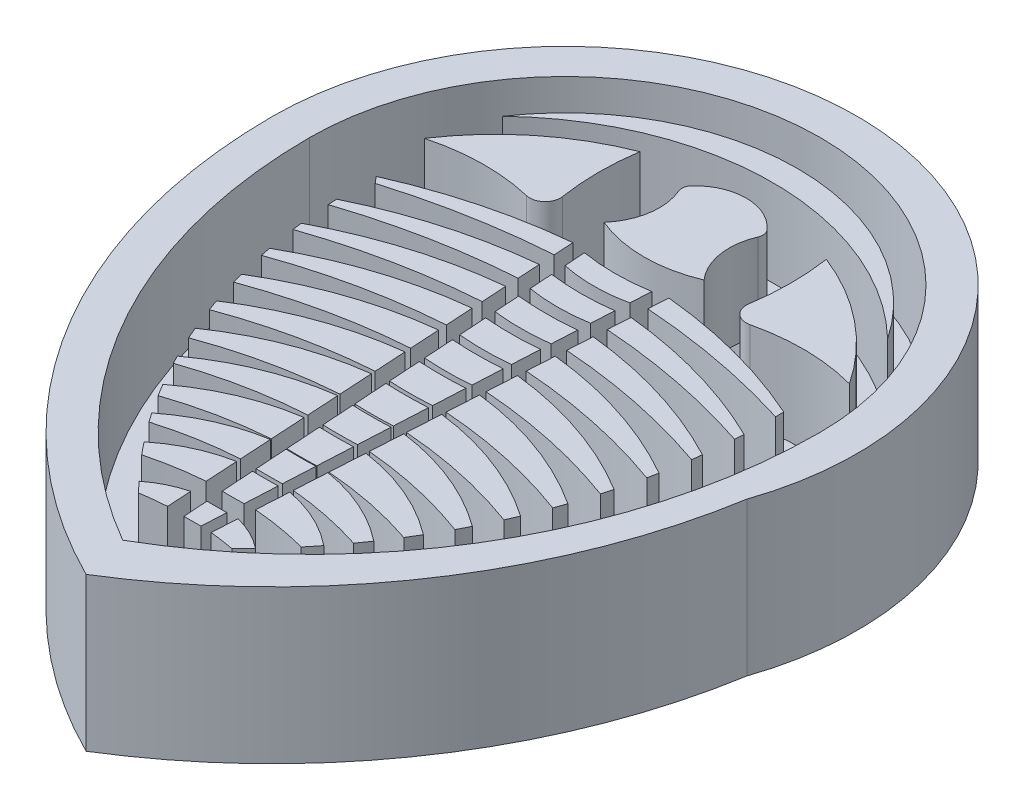
SolidWorks part; units mm, degrees
ref_plane "Přední rovina" through (0, 0, 0) normal (0, 0, 1) x (1, 0, 0)
ref_plane "Horní rovina" through (0, 0, 0) normal (0, 1, 0) x (1, 0, 0)
ref_plane "Pravá rovina" through (0, 0, 0) normal (1, 0, 0) x (0, 0, -1)
sketch "Skica1" plane through (0, 0, 0) normal (0, 1, 0) x (1, 0, 0)
  line L0 (3.5212, 0.7459) -> (3.5212, -1.0568)
  line L1 (2.9157, -3.7821) -> (1.736, -4.9619)
  line L2 (-3.4891, 0.7312) -> (-3.4891, -1.0783)
  line L3 (-1.7389, -4.9589) -> (-2.9157, -3.7821)
  line L7 (-3.4144, 2.0461) -> (3.4576, 2.0461)
  arc A0 (5, 0) -> (-5, 0) centre (0, 0) ccw
  arc A1 (-5, 0) -> (0, -8.6603) centre (5, 0) ccw
  arc A2 (0, -8.6603) -> (5, 0) centre (-5, 0) ccw
  arc A3 (1.736, -4.9619) -> (3.5212, 0.7459) centre (4.6199, -2.7308) cw
  arc A4 (2.9157, -3.7821) -> (3.5212, -1.0568) centre (4.6199, -2.7308) cw
  arc A5 (-3.4891, -1.0783) -> (-2.9157, -3.7821) centre (-4.6199, -2.7308) cw
  arc A6 (-3.4891, 0.7312) -> (-1.7389, -4.9589) centre (-4.6199, -2.7308) cw
  spline S0 degree 2 poles (-3.4144, 2.0461) (0.0191, 3.7316) (3.4576, 2.0461) knots 0 0 0 1 1 1
  dimension "D1" = 10
extrude "Přidat vysunutím1" add sketch "Skica1" against normal blind 1
sketch "Skica2" plane through (0, 0, 0) normal (0, 1, 0) x (1, 0, 0)
  line L0 (-0.9396, 1.0946) -> (-0.9163, 0.7054)
  line L1 (0.9396, 1.0946) -> (0.9163, 0.7054)
  line L2 (-0.4639, -6.8657) -> (-0.435, -7.3481)
  line L3 (-0.521, -5.9092) -> (-0.4831, -6.5437)
  line L4 (0.521, -5.9092) -> (0.4831, -6.5437)
  line L5 (-0.5631, -5.2058) -> (-0.5258, -5.8294)
  line L6 (-0.605, -4.5041) -> (-0.5642, -5.1865)
  line L7 (0.605, -4.5041) -> (0.5642, -5.1865)
  line L8 (0.6469, -3.8031) -> (0.6088, -4.4409)
  line L9 (-0.6469, -3.8031) -> (-0.6097, -4.4257)
  line L10 (-0.6887, -3.1028) -> (-0.6498, -3.7549)
  line L11 (0.6887, -3.1028) -> (0.6498, -3.7549)
  line L12 (0.7306, -2.4028) -> (0.6935, -3.0231)
  line L13 (-0.7306, -2.4028) -> (-0.6935, -3.0231)
  line L14 (-0.7724, -1.703) -> (-0.7376, -2.2844)
  line L15 (0.7724, -1.703) -> (0.7376, -2.2844)
  line L16 (0.8142, -1.0034) -> (0.7821, -1.5408)
  line L17 (-0.8142, -1.0034) -> (-0.7821, -1.5408)
  line L18 (-0.856, -0.304) -> (-0.8267, -0.7938)
  line L19 (0.856, -0.304) -> (0.8267, -0.7938)
  line L20 (0.8978, 0.3954) -> (0.8715, -0.0448)
  line L21 (-0.8978, 0.3954) -> (-0.8715, -0.0448)
  line L22 (0.4639, -6.8657) -> (0.434, -7.3648)
  line L23 (0.5631, -5.2058) -> (0.5249, -5.8452)
  line L24 (-0.6539, 1.0367) -> (-0.6272, 0.6279)
  line L25 (0.6621, 1.0381) -> (0.641, 0.6309)
  line L26 (-0.6089, 0.3483) -> (-0.5795, -0.1033)
  line L27 (0.6264, 0.3507) -> (0.6031, -0.0994)
  line L28 (0.5906, -0.3401) -> (0.5649, -0.8356)
  line L29 (-0.5638, -0.3429) -> (-0.5314, -0.8398)
  line L30 (0.5547, -1.0329) -> (0.5266, -1.5735)
  line L31 (-0.5186, -1.0361) -> (-0.4832, -1.5778)
  line L32 (-0.4732, -1.7307) -> (-0.4351, -2.3147)
  line L33 (0.5186, -1.7274) -> (0.4884, -2.3105)
  line L34 (-0.4279, -2.4264) -> (-0.3873, -3.0482)
  line L35 (0.4826, -2.4231) -> (0.4504, -3.0442)
  line L36 (-0.3369, -3.8204) -> (-0.2962, -4.4435)
  line L37 (0.4103, -3.8173) -> (0.378, -4.4401)
  line L38 (0.4464, -3.1197) -> (0.4126, -3.7721)
  line L39 (-0.3824, -3.123) -> (-0.3398, -3.7759)
  line L40 (0.3377, -5.2158) -> (0.3054, -5.8391)
  line L41 (-0.2456, -5.2184) -> (-0.205, -5.8419)
  line L42 (0.374, -4.5159) -> (0.3387, -5.1981)
  line L43 (-0.2913, -4.5188) -> (-0.2468, -5.2012)
  line L44 (-0.1999, -5.9198) -> (-0.1585, -6.554)
  line L45 (0.3013, -5.9174) -> (0.2685, -6.5517)
  line L46 (-0.1376, -6.874) -> (-0.1061, -7.3562)
  line L47 (0.2518, -6.8721) -> (0.2268, -7.3544)
  arc A0 (3.7723, 2.5471) -> (-3.7723, 2.5471) centre (0, 0) ccw
  arc A1 (3.7723, 2.5471) -> (-3.7723, 2.5471) centre (0, -1.3616) ccw
  arc A2 (-1.826, 3.293) -> (-4.1627, 1.4083) centre (0, -1.3616) ccw
  arc A7 (4.1627, 1.4083) -> (2.1882, 1.4375) centre (3.118, -2.4529) ccw
  arc A8 (-1.826, 3.293) -> (-1.8221, 1.7756) centre (3.118, 2.5471) ccw
  arc A9 (4.1627, 1.4083) -> (1.826, 3.293) centre (0, -1.3616) ccw
  arc A10 (1.8221, 1.7756) -> (1.826, 3.293) centre (-3.118, 2.5471) ccw
  arc A11 (-2.1882, 1.4375) -> (-1.8221, 1.7756) centre (-2.1185, 1.7293) ccw
  arc A12 (1.8221, 1.7756) -> (2.1882, 1.4375) centre (2.1185, 1.7293) ccw
  arc A13 (-2.1882, 1.4375) -> (-4.1627, 1.4083) centre (-3.118, -2.4529) ccw
  arc A15 (-0.9784, 1.7445) -> (-0.778, 3.0046) centre (-1.8819, 2.5341) ccw
  arc A16 (0.778, 3.0046) -> (0.9784, 1.7445) centre (1.8819, 2.5341) ccw
  arc A17 (-0.7425, 3.2169) -> (-0.778, 3.0046) centre (-0.594, 3.083) ccw
  arc A18 (0.778, 3.0046) -> (0.7425, 3.2169) centre (0.594, 3.083) ccw
  arc A20 (3.996, 0.288) -> (0.9396, 1.0946) centre (0, -8.6603) ccw
  arc A21 (-0.9784, 1.7445) -> (0.9784, 1.7445) centre (0, 4.0705) ccw
  arc A22 (0.7425, 3.2169) -> (-0.7425, 3.2169) centre (0, 2.5471) ccw
  arc A23 (3.989, -0.4811) -> (0.8978, 0.3954) centre (0, -8.6603) ccw
  arc A24 (3.9271, -1.2348) -> (0.856, -0.304) centre (0, -8.6603) ccw
  arc A25 (3.8134, -1.9708) -> (0.8142, -1.0034) centre (0, -8.6603) ccw
  arc A26 (3.6503, -2.6874) -> (0.7724, -1.703) centre (0, -8.6603) ccw
  arc A27 (3.4403, -3.3825) -> (0.7306, -2.4028) centre (0, -8.6603) ccw
  arc A28 (3.1856, -4.0546) -> (0.6887, -3.1028) centre (0, -8.6603) ccw
  arc A29 (2.8883, -4.702) -> (0.6469, -3.8031) centre (0, -8.6603) ccw
  arc A30 (2.5505, -5.3234) -> (0.605, -4.5041) centre (0, -8.6603) ccw
  arc A31 (2.1739, -5.9172) -> (0.5631, -5.2058) centre (0, -8.6603) ccw
  arc A32 (1.76, -6.4825) -> (0.521, -5.9092) centre (0, -8.6603) ccw
  arc A33 (1.1422, -7.2005) -> (0.4639, -6.8657) centre (0, -8.6603) ccw
  arc A34 (-4.9974, -0.2302) -> (0, -8.6603) centre (5, 0) ccw
  arc A35 (0, -8.6603) -> (4.9974, -0.2302) centre (-5, 0) ccw
  arc A36 (3.9992, 0.1259) -> (0.9163, 0.7054) centre (0, -12.6603) ccw
  arc A37 (3.9794, -0.6572) -> (0.8715, -0.0448) centre (0, -12.6603) ccw
  arc A38 (3.903, -1.4236) -> (0.8267, -0.7938) centre (0, -12.6603) ccw
  arc A39 (3.773, -2.1713) -> (0.7821, -1.5408) centre (0, -12.6603) ccw
  arc A40 (3.5921, -2.8981) -> (0.7376, -2.2844) centre (0, -12.6603) ccw
  arc A41 (3.3628, -3.6022) -> (0.6935, -3.0231) centre (0, -12.6603) ccw
  arc A42 (3.0872, -4.2819) -> (0.6498, -3.7549) centre (0, -12.6603) ccw
  arc A43 (2.7721, -4.9273) -> (0.6088, -4.4409) centre (-0.103, -12.6603) ccw
  arc A44 (2.4059, -5.5618) -> (0.5642, -5.1865) centre (0, -12.6603) ccw
  arc A45 (2.01, -6.1506) -> (0.5249, -5.8452) centre (-0.103, -12.6603) ccw
  arc A46 (1.5622, -6.7269) -> (0.4831, -6.5437) centre (0, -12.6603) ccw
  arc A47 (0.9136, -7.4357) -> (0.434, -7.3648) centre (-0.103, -12.6603) ccw
  arc A51 (0.9136, -7.4357) -> (1.1422, -7.2005) centre (-6.5, 0) ccw
  arc A52 (-0.9396, 1.0946) -> (-3.996, 0.288) centre (0, -8.6603) ccw
  arc A53 (-1.1422, -7.2005) -> (-0.9445, -7.4046) centre (6.5, 0) ccw
  arc A54 (-1.76, -6.4825) -> (-1.5622, -6.7269) centre (6.5, 0) ccw
  arc A55 (-2.1739, -5.9172) -> (-2.0475, -6.0984) centre (6.5, 0) ccw
  arc A56 (-2.5505, -5.3234) -> (-2.4059, -5.5618) centre (6.5, 0) ccw
  arc A57 (-2.8883, -4.702) -> (-2.8049, -4.8651) centre (6.5, 0) ccw
  arc A58 (-3.1856, -4.0546) -> (-3.0872, -4.2819) centre (6.5, 0) ccw
  arc A59 (-3.4403, -3.3825) -> (-3.3628, -3.6022) centre (6.5, 0) ccw
  arc A60 (-3.6503, -2.6874) -> (-3.5921, -2.8981) centre (6.5, 0) ccw
  arc A61 (-3.8134, -1.9708) -> (-3.773, -2.1713) centre (6.5, 0) ccw
  arc A62 (-3.9271, -1.2348) -> (-3.903, -1.4236) centre (6.5, 0) ccw
  arc A63 (-3.989, -0.4811) -> (-3.9794, -0.6572) centre (6.5, 0) ccw
  arc A64 (3.9992, 0.1259) -> (3.996, 0.288) centre (-6.5, 0) ccw
  arc A65 (3.9794, -0.6572) -> (3.989, -0.4811) centre (-6.5, 0) ccw
  arc A66 (3.903, -1.4236) -> (3.9271, -1.2348) centre (-6.5, 0) ccw
  arc A67 (3.773, -2.1713) -> (3.8134, -1.9708) centre (-6.5, 0) ccw
  arc A68 (3.5921, -2.8981) -> (3.6503, -2.6874) centre (-6.5, 0) ccw
  arc A69 (3.3628, -3.6022) -> (3.4403, -3.3825) centre (-6.5, 0) ccw
  arc A70 (3.0872, -4.2819) -> (3.1856, -4.0546) centre (-6.5, 0) ccw
  arc A71 (2.7721, -4.9273) -> (2.8883, -4.702) centre (-6.5, 0) ccw
  arc A72 (2.4059, -5.5618) -> (2.5505, -5.3234) centre (-6.5, 0) ccw
  arc A73 (2.01, -6.1506) -> (2.1739, -5.9172) centre (-6.5, 0) ccw
  arc A74 (1.5622, -6.7269) -> (1.76, -6.4825) centre (-6.5, 0) ccw
  arc A75 (-0.9163, 0.7054) -> (-3.9992, 0.1259) centre (0, -12.6603) ccw
  arc A76 (-0.8978, 0.3954) -> (-3.989, -0.4811) centre (0, -8.6603) ccw
  arc A77 (-0.8715, -0.0448) -> (-3.9794, -0.6572) centre (0, -12.6603) ccw
  arc A78 (-0.856, -0.304) -> (-3.9271, -1.2348) centre (0, -8.6603) ccw
  arc A79 (-0.8267, -0.7938) -> (-3.903, -1.4236) centre (0, -12.6603) ccw
  arc A80 (-0.8142, -1.0034) -> (-3.8134, -1.9708) centre (0, -8.6603) ccw
  arc A81 (-0.7821, -1.5408) -> (-3.773, -2.1713) centre (0, -12.6603) ccw
  arc A82 (-0.7724, -1.703) -> (-3.6503, -2.6874) centre (0, -8.6603) ccw
  arc A83 (-0.7376, -2.2844) -> (-3.5921, -2.8981) centre (0, -12.6603) ccw
  arc A84 (-0.7306, -2.4028) -> (-3.4403, -3.3825) centre (0, -8.6603) ccw
  arc A85 (-0.6935, -3.0231) -> (-3.3628, -3.6022) centre (0, -12.6603) ccw
  arc A86 (-0.6887, -3.1028) -> (-3.1856, -4.0546) centre (0, -8.6603) ccw
  arc A87 (-0.6498, -3.7549) -> (-3.0872, -4.2819) centre (0, -12.6603) ccw
  arc A88 (-0.6469, -3.8031) -> (-2.8883, -4.702) centre (0, -8.6603) ccw
  arc A89 (-0.6097, -4.4257) -> (-2.8049, -4.8651) centre (-0.103, -12.6603) ccw
  arc A90 (-0.605, -4.5041) -> (-2.5505, -5.3234) centre (0, -8.6603) ccw
  arc A91 (-0.5642, -5.1865) -> (-2.4059, -5.5618) centre (0, -12.6603) ccw
  arc A92 (-0.5631, -5.2058) -> (-2.1739, -5.9172) centre (0, -8.6603) ccw
  arc A93 (-0.5258, -5.8294) -> (-2.0475, -6.0984) centre (-0.103, -12.6603) ccw
  arc A94 (-0.521, -5.9092) -> (-1.76, -6.4825) centre (0, -8.6603) ccw
  arc A95 (-0.4831, -6.5437) -> (-1.5622, -6.7269) centre (0, -12.6603) ccw
  arc A96 (-0.4639, -6.8657) -> (-1.1422, -7.2005) centre (0, -8.6603) ccw
  arc A97 (-0.435, -7.3481) -> (-0.9445, -7.4046) centre (-0.103, -12.6603) ccw
  arc A98 (-3.996, 0.288) -> (-3.9992, 0.1259) centre (6.5, 0) ccw
  arc A100 (5, 0) -> (-5, 0) centre (0, 0) ccw construction
  arc A108 (-0.2913, -4.5188) -> (0.374, -4.5159) centre (0, 5) ccw
  arc A111 (-0.1376, -6.874) -> (0.2518, -6.8721) centre (0, 5) ccw
  arc A112 (-0.6539, 1.0367) -> (0.6621, 1.0381) centre (0, 5) ccw
  arc A113 (-0.5186, -1.0361) -> (0.5547, -1.0329) centre (0, 5) ccw
  arc A114 (-0.4732, -1.7307) -> (0.5186, -1.7274) centre (0, 5) ccw
  arc A115 (-0.5795, -0.1033) -> (0.6031, -0.0994) centre (0, 3.5471) ccw
  arc A116 (-0.6089, 0.3483) -> (0.6264, 0.3507) centre (0, 5) ccw
  arc A117 (-0.5638, -0.3429) -> (0.5906, -0.3401) centre (0, 5) ccw
  arc A118 (-0.4279, -2.4264) -> (0.4826, -2.4231) centre (0, 5) ccw
  arc A119 (-0.4351, -2.3147) -> (0.4884, -2.3105) centre (0, 3.5471) ccw
  arc A120 (-0.3873, -3.0482) -> (0.4504, -3.0442) centre (0, 3.5471) ccw
  arc A121 (-0.3824, -3.123) -> (0.4464, -3.1197) centre (0, 5) ccw
  arc A122 (-0.3369, -3.8204) -> (0.4103, -3.8173) centre (0, 5) ccw
  arc A123 (-0.1999, -5.9198) -> (0.3013, -5.9174) centre (0, 5) ccw
  arc A124 (-0.2456, -5.2184) -> (0.3377, -5.2158) centre (0, 5) ccw
  arc A125 (-0.1585, -6.554) -> (0.2685, -6.5517) centre (0, 3.5471) ccw
  arc A129 (-3.9876, 0.2918) -> (-3.8789, 0.163) centre (0, 3.5471) ccw
  arc A134 (-0.2468, -5.2012) -> (0.3387, -5.1981) centre (0, 3.5471) ccw
  arc A138 (-0.6272, 0.6279) -> (0.641, 0.6309) centre (0, 3.5471) ccw
  arc A139 (-0.4832, -1.5778) -> (0.5266, -1.5735) centre (0, 3.5471) ccw
  arc A140 (-0.2962, -4.4435) -> (0.378, -4.4401) centre (0, 3.5471) ccw
  arc A141 (-0.5314, -0.8398) -> (0.5649, -0.8356) centre (0, 3.5471) ccw
  arc A142 (-0.3398, -3.7759) -> (0.4126, -3.7721) centre (0, 3.5471) ccw
  arc A143 (-0.205, -5.8419) -> (0.3054, -5.8391) centre (0, 3.5471) ccw
  arc A144 (-0.1061, -7.3562) -> (0.2268, -7.3544) centre (0, 3.5471) ccw
  point P44 (0, -12.6603)
  dimension "D1" = 4
  dimension "D4" = 1.5
  dimension "D5" = 1.5
extrude "Přidat vysunutím2" add sketch "Skica2" along normal blind 1.7 contours A97 L2 A96 A53 | A95 L3 A94 A54 | A93 L5 A92 A55 | A91 L6 A90 A56 | A89 L9 A88 A57 | A87 L10 A86 A58 | A85 L13 A84 A59 | A83 L14 A82 A60 | A81 L17 A80 A61 | A77 L21 A76 A63 | A52 A129 A75 L0 | A13 A11 A8 A2 | A1 A0 | A18 A22 A17 A15 A21 A16 | A10 A12 A7 A9 | L24 A138 L25 A112 | A116 L26 A115 L27 | L29 A141 L28 A117 | L31 A139 L30 A113 | L32 A119 L33 A114 | L34 A120 L35 A118 | L39 A142 L38 A121 | L36 A140 L37 A122 | L43 A134 L42 A108 | L41 A143 L40 A124 | L44 A125 L45 A123 | L46 A144 L47 A111 | A47 A51 A33 L22 | A46 A74 A32 L4 | A45 A73 A31 L23 | A44 A72 A30 L7 | A43 A71 A29 L8 | A42 A70 A28 L11 | A41 A69 A27 L12 | A40 A68 A26 L15 | A39 A67 A25 L16 | A38 A66 A24 L19 | A37 A65 A23 L20 | A78 A62 A79 L18 | A36 L1 A20 A64
ref_plane "Rovina1" through (0, -1, 0) normal (0, -1, 0) x (-1, 0, 0)
sketch "Sketch1" plane through (0, -1, 0) normal (0, -1, 0) x (1, 0, 0)
  arc A0 (-5, 0) -> (5, 0) centre (0, 0) ccw construction
  arc A1 (0, 8.6603) -> (-5, 0) centre (5, 0) ccw construction
  arc A3 (-5, 0) -> (5, 0) centre (0, 0) ccw
  arc A4 (0, 8.6603) -> (-5, 0) centre (5, 0) ccw
  arc A6 (-5.7225, 0) -> (5.4144, 1.8523) centre (0, 0) ccw
  arc A7 (0.2212, 9.5986) -> (-5.7225, 0) centre (5, 0) ccw
  arc A8 (5.4144, 1.8523) -> (0.2212, 9.5986) centre (-5.7225, 0) ccw
  point P5 (5.5674, 0)
  point P7 (0, 9.23)
  point P8 (-5.7225, 0)
  arc M5 (5, 0) -> (0, 8.6603) centre (-5, 0) ccw
  arc M6 (0, 8.6603) -> (-5, 0) centre (5, 0) ccw
  arc M7 (-5, 0) -> (5, 0) centre (0, 0) ccw
extrude "Boss-Extrude1" add sketch "Sketch1" against normal blind 3 contours A6 A8 A7 M5 M7 M6
